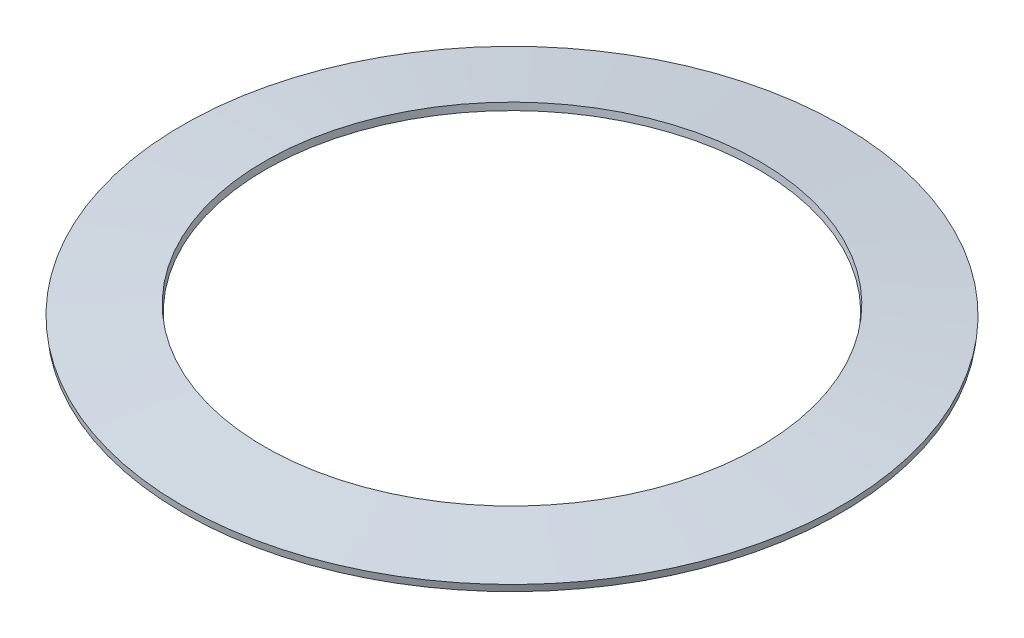
SolidWorks part; units mm, degrees
ref_plane "Front" through (0, 0, 0) normal (0, 0, 1) x (1, 0, 0)
ref_plane "Top" through (0, 0, 0) normal (0, 1, 0) x (1, 0, 0)
ref_plane "Right" through (0, 0, 0) normal (1, 0, 0) x (0, 0, -1)
sketch "Sketch1" plane through (0, 0, 0) normal (0, 0, 1) x (1, 0, 0)
  line L0 (33.667, 0) -> (25.25, 1.0049)
  line L1 (25.25, 1.0049) -> (25.333, 1.7)
  line L2 (25.333, 1.7) -> (33.75, 0.6951)
  line L3 (33.75, 0.6951) -> (33.667, 0)
  line L4 (0, 0) -> (0, 1.7) construction
  dimension "ID" = 50.5
  dimension "OD" = 67.5
  dimension "Thickness" = 0.7
  dimension "Height" = 1.7
revolve "Revolve1" add sketch "Sketch1" angle 360 about L4
